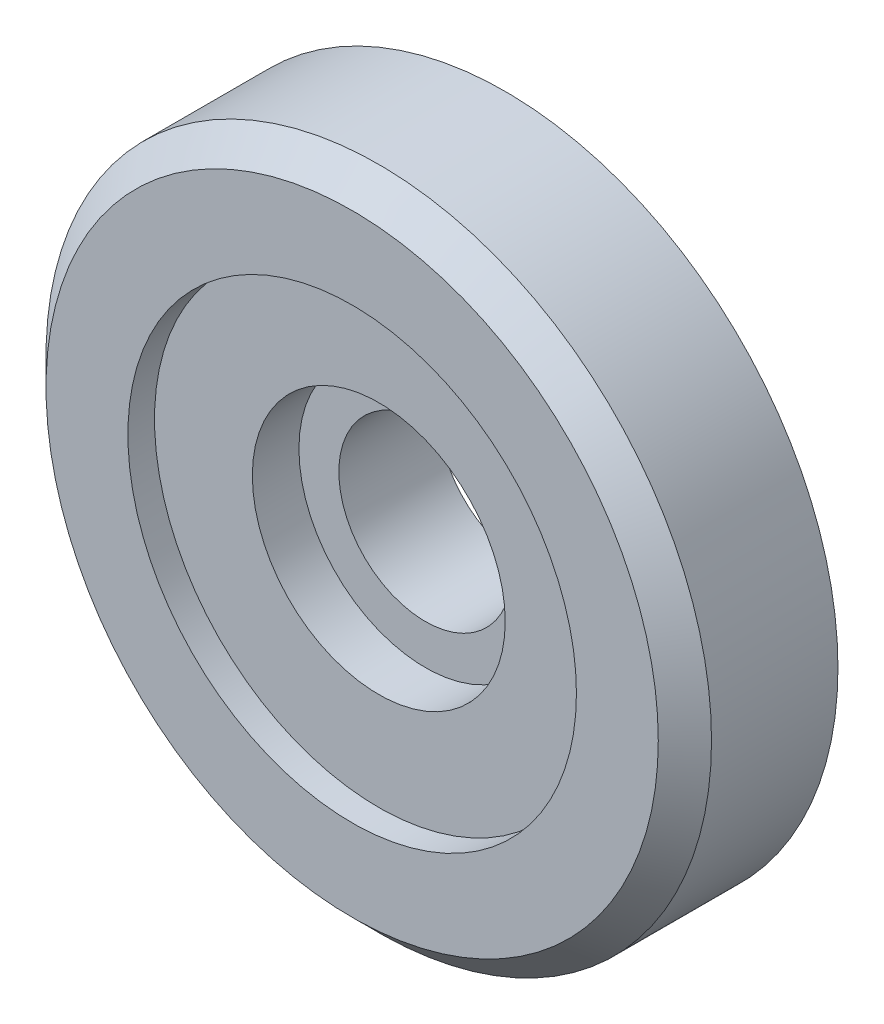
SolidWorks part; units mm, degrees
ref_plane "Alzado" through (0, 0, 0) normal (0, 0, 1) x (1, 0, 0)
ref_plane "Planta" through (0, 0, 0) normal (0, 1, 0) x (1, 0, 0)
ref_plane "Vista lateral" through (0, 0, 0) normal (1, 0, 0) x (0, 0, -1)
sketch "Croquis1" plane through (0, 0, 0) normal (0, 0, 1) x (1, 0, 0)
  circle A0 centre (0, 0) radius 25
  dimension "D1" = 50
extrude "Saliente-Extruir1" add sketch "Croquis1" against normal blind 11.5
sketch "Croquis2" plane through (0, 0, 0) normal (0, 0, 1) x (1, 0, 0)
  circle A0 centre (0, 0) radius 16.85
  dimension "D1" = 33.7
extrude "Cortar-Extruir1" cut sketch "Croquis2" against normal blind 2
sketch "Croquis3" plane through (0, 0, -2) normal (0, 0, 1) x (1, 0, 0)
  circle A0 centre (0, 0) radius 9.5
  dimension "D1" = 19
extrude "Cortar-Extruir2" cut sketch "Croquis3" against normal blind 3.5
sketch "Croquis4" plane through (0, 0, -5.5) normal (0, 0, 1) x (1, 0, 0)
  circle A0 centre (0, 0) radius 6.5
  dimension "D1" = 13
extrude "Cortar-Extruir3" cut sketch "Croquis4" against normal up to next
sketch "Croquis5" plane through (0, 0, -11.5) normal (0, 0, -1) x (-1, 0, 0)
  circle A0 centre (0, 0) radius 6.5
  circle A1 centre (0, 0) radius 11
  dimension "D1" = 13
  dimension "D2" = 22
extrude "Saliente-Extruir2" add sketch "Croquis5" along normal blind 1.5
chamfer "Chaflán1" distance 2 angle 45 1 edges at (25, 0, 0)
